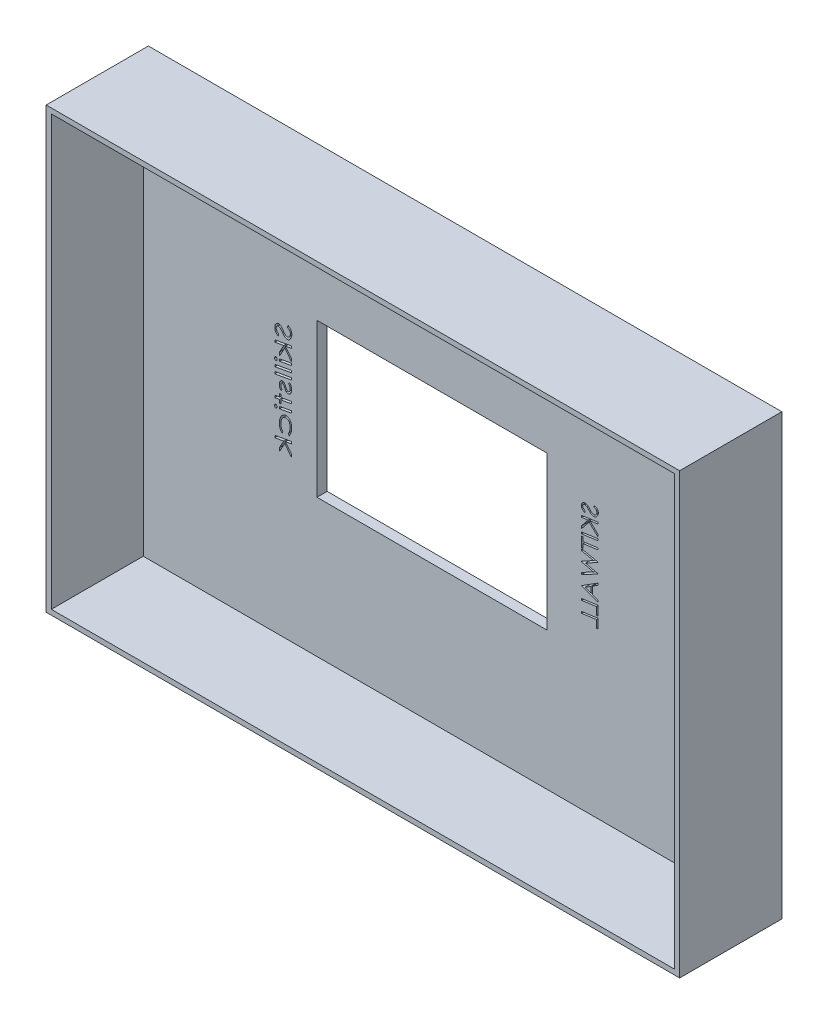
SolidWorks part; units mm, degrees
ref_plane "Front Plane" through (0, 0, 0) normal (0, 0, 1) x (1, 0, 0)
ref_plane "Top Plane" through (0, 0, 0) normal (0, 1, 0) x (1, 0, 0)
ref_plane "Right Plane" through (0, 0, 0) normal (1, 0, 0) x (0, 0, -1)
sketch "Sketch1" plane through (0, 0, 0) normal (0, 0, 1) x (1, 0, 0)
  line L1 (-51.3197, 37.019) -> (72.6803, 37.019)
  line L2 (-51.3197, 37.019) -> (-51.3197, -48.981)
  line L3 (-51.3197, -48.981) -> (72.6803, -48.981)
  line L4 (72.6803, 37.019) -> (72.6803, -48.981)
  dimension "D1" = 124
  dimension "D2" = 86
extrude "Boss-Extrude1" add sketch "Sketch1" along normal blind 20
sketch "Sketch2" plane through (0, 0, 20) normal (0, 0, 1) x (1, 0, 0)
  line L0 (-51.3197, 37.019) -> (-51.3197, -48.981) construction
  line L1 (-50.3197, 36.019) -> (71.6803, 36.019)
  line L2 (-50.3197, 36.019) -> (-50.3197, -47.981)
  line L3 (-50.3197, -47.981) -> (71.6803, -47.981)
  line L4 (71.6803, 36.019) -> (71.6803, -47.981)
  line L5 (72.6803, 37.019) -> (-51.3197, 37.019) construction
  dimension "D1" = 122
  dimension "D2" = 84
  dimension "D3" = 1
  dimension "D4" = 1
extrude "Cut-Extrude1" cut sketch "Sketch2" against normal blind 18
sketch "Sketch3" plane through (0, 0, 0) normal (0, 0, -1) x (-1, 0, 0)
  line L0 (51.3197, 37.019) -> (51.3197, -48.981) construction
  line L1 (-28.6803, 9.019) -> (16.3197, 9.019)
  line L2 (-28.6803, 9.019) -> (-28.6803, -20.981)
  line L3 (-28.6803, -20.981) -> (16.3197, -20.981)
  line L4 (16.3197, 9.019) -> (16.3197, -20.981)
  line L6 (-72.6803, 37.019) -> (51.3197, 37.019) construction
  text T0 "                   <i>Skillstick</i>" font "Century Gothic" height 3.175
  text T1 "                        <i>SKITWALL</i>" font "Century Gothic" height 3.175
  dimension "D1" = 45
  dimension "D2" = 35
  dimension "D3" = 30
  dimension "D4" = 28
extrude "Cut-Extrude3" cut sketch "Sketch3" against normal blind 2
